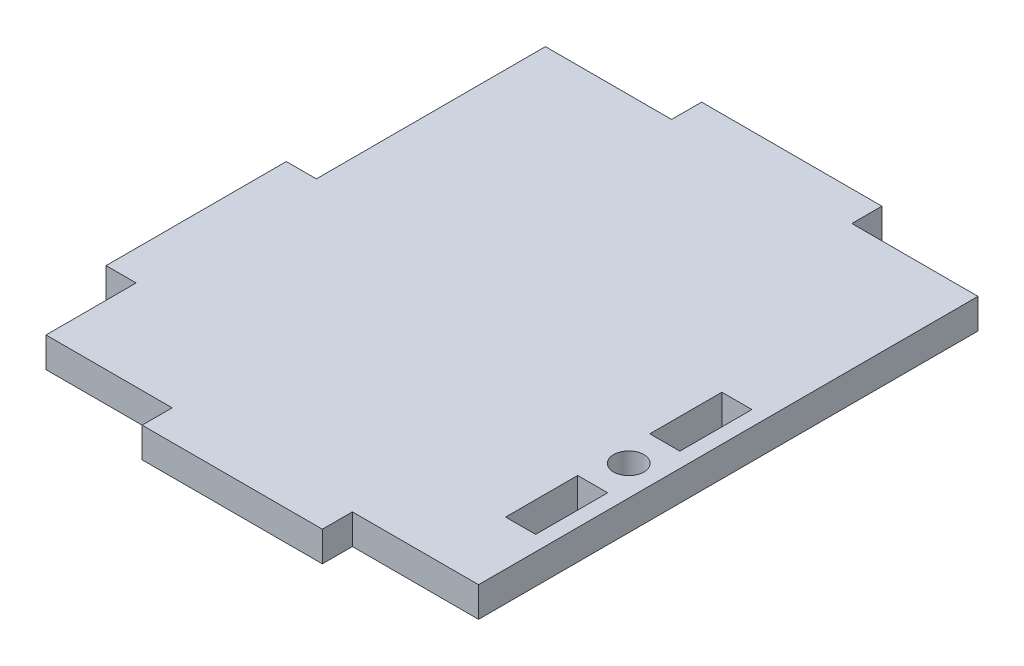
SolidWorks part; units mm, degrees
ref_plane "Front Plane" through (0, 0, 0) normal (0, 0, 1) x (1, 0, 0)
ref_plane "Top Plane" through (0, 0, 0) normal (0, 1, 0) x (1, 0, 0)
ref_plane "Right Plane" through (0, 0, 0) normal (1, 0, 0) x (0, 0, -1)
sketch "Sketch1" plane through (0, 0, 0) normal (0, 1, 0) x (1, 0, 0)
  line L0 (0, 0) -> (13.335, 0)
  line L1 (13.335, 0) -> (13.335, -3.175)
  line L2 (13.335, -3.175) -> (32.385, -3.175)
  line L3 (32.385, -3.175) -> (32.385, 0)
  line L4 (32.385, 0) -> (45.72, 0)
  line L5 (45.72, 0) -> (45.72, 52.7888)
  line L6 (45.72, 52.7888) -> (32.385, 52.7888)
  line L7 (32.385, 52.7888) -> (32.385, 55.9638)
  line L8 (32.385, 55.9638) -> (13.335, 55.9638)
  line L9 (13.335, 55.9638) -> (13.335, 52.7888)
  line L10 (13.335, 52.7888) -> (0, 52.7888)
  line L11 (0, 52.7888) -> (0, 28.575)
  line L12 (0, 28.575) -> (-3.175, 28.575)
  line L13 (-3.175, 28.575) -> (-3.175, 9.525)
  line L14 (-3.175, 9.525) -> (0, 9.525)
  line L15 (0, 9.525) -> (0, 0)
  line L17 (40.9575, 30.48) -> (44.1325, 30.48)
  line L18 (40.9575, 30.48) -> (40.9575, 22.86)
  line L19 (40.9575, 22.86) -> (44.1325, 22.86)
  line L20 (44.1325, 30.48) -> (44.1325, 22.86)
  line L21 (40.9575, 15.24) -> (44.1325, 15.24)
  line L22 (40.9575, 15.24) -> (40.9575, 7.62)
  line L23 (40.9575, 7.62) -> (44.1325, 7.62)
  line L24 (44.1325, 15.24) -> (44.1325, 7.62)
  dimension "D1" = 3.175
  dimension "D2" = 19.05
  dimension "D3" = 19.05
  dimension "D4" = 45.72
  dimension "D5" = 52.7888
  dimension "D6" = 9.525
  dimension "D7" = 3.175
  dimension "D8" = 1.5875
  dimension "D9" = 7.62
  dimension "D10" = 7.62
  dimension "D11" = 7.62
extrude "Boss-Extrude1" add sketch "Sketch1" along normal blind 3.175
hole_wizard "M3 Clearance Hole1" positions "Sketch3" profile "Sketch2" hole size "M3" standard "ANSI Metric" end condition through all
sketch "Sketch3" plane through (0, 3.175, 0) normal (0, 1, 0) x (1, 0, 0)
  line L0 (42.545, 22.86) -> (42.545, 15.24) construction
  line L1 (40.9575, 22.86) -> (44.1325, 22.86) construction
  line L2 (44.1325, 15.24) -> (40.9575, 15.24) construction
  point P0 (42.545, 19.05)
  point P12 (42.545, 19.05)
sketch "Sketch2" plane through (42.545, 3.175, -19.05) normal (1, 0, 0) x (0, 0, 1)
  line L0 (0, 0) -> (0, 3.175)
  line L1 (0, 3.175) -> (1.6, 3.175)
  line L2 (1.6, 3.175) -> (1.6, 0)
  line L5 (1.6, 0) -> (0, 0)
  line L11 (0, -6.35) -> (0, 107.95) construction
  dimension "Thru Hole Dia." = 3.2
  dimension "Thru Hole Depth" = 3.175
